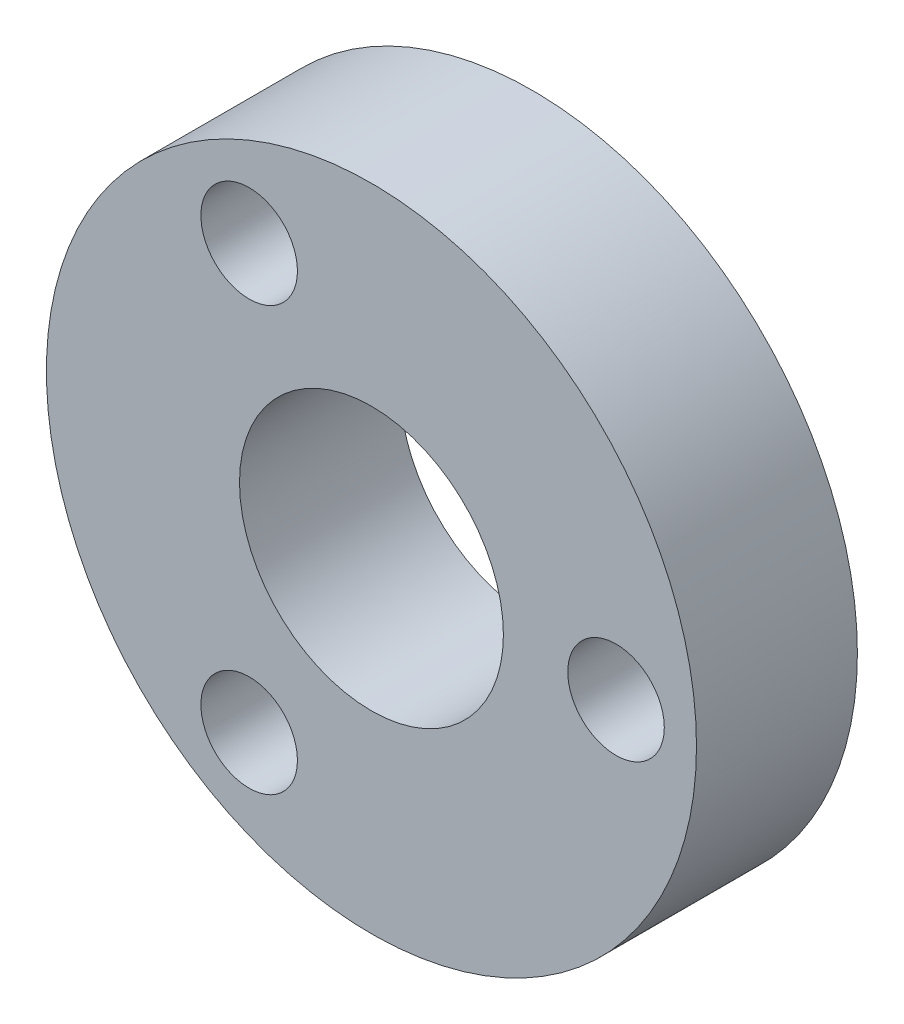
SolidWorks part; units mm, degrees
ref_plane "Front Plane" through (0, 0, 0) normal (0, 0, 1) x (1, 0, 0)
ref_plane "Top Plane" through (0, 0, 0) normal (0, 1, 0) x (1, 0, 0)
ref_plane "Right Plane" through (0, 0, 0) normal (1, 0, 0) x (0, 0, -1)
sketch "Sketch2" plane through (0, 0, 0) normal (0, 0, 1) x (1, 0, 0)
  circle A0 centre (0, 0) radius 4.1
  circle A1 centre (0, 0) radius 10.1
  circle A2 centre (0, 0) radius 7.6 construction
  circle A3 centre (7.6, 0) radius 1.5
  circle A4 centre (-3.8, -6.5818) radius 1.5
  circle A5 centre (-3.8, 6.5818) radius 1.5
  point P7 (0, 0)
  point P8 (-3.8, 6.5818)
  point P16 (0, 0)
  dimension "D1" = 8.2
  dimension "D2" = 6
  dimension "D3" = 3.5
  dimension "D4" = 3
  dimension "D5" = 3
extrude "Boss-Extrude1" add sketch "Sketch2" along normal blind 5
